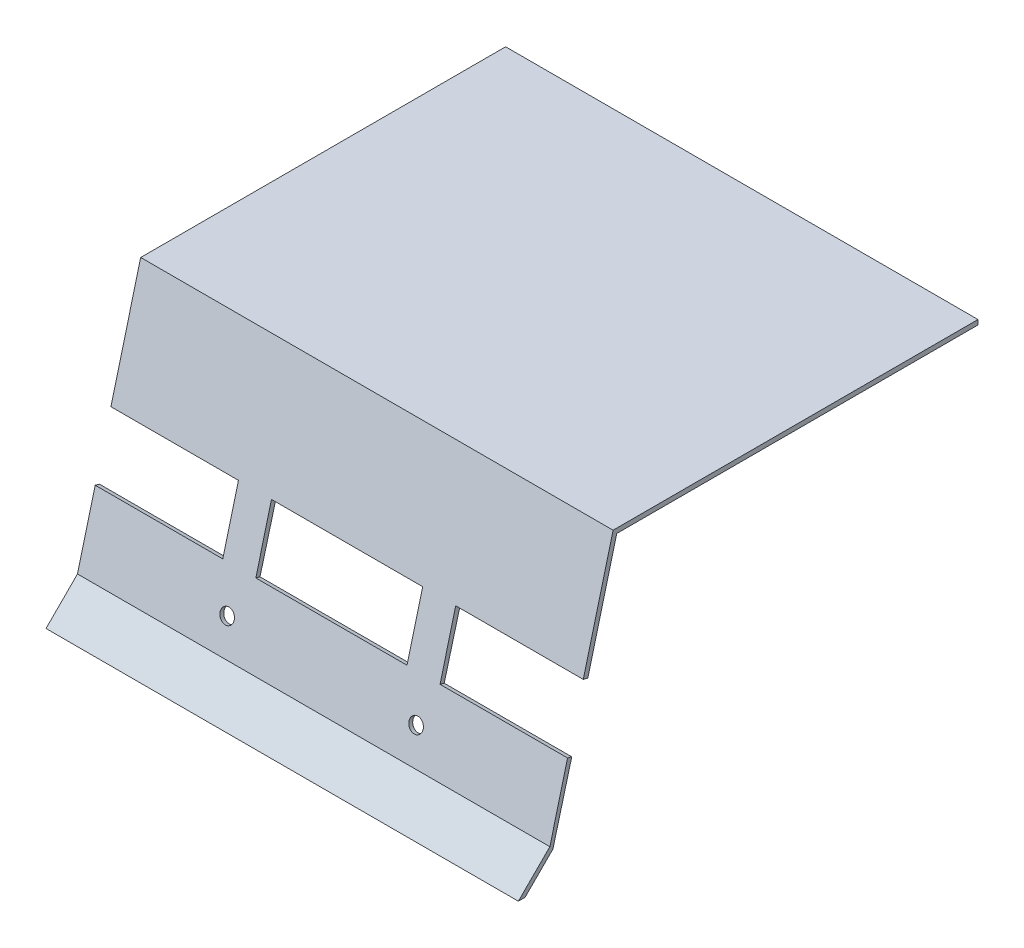
SolidWorks part; units mm, degrees
ref_plane "Plano frontal" through (0, 0, 0) normal (0, 0, 1) x (1, 0, 0)
ref_plane "Plano superior" through (0, 0, 0) normal (0, 1, 0) x (1, 0, 0)
ref_plane "Plano direito" through (0, 0, 0) normal (1, 0, 0) x (0, 0, -1)
sketch "Esboço1" plane through (0, 0, 0) normal (1, 0, 0) x (0, 0, -1)
  line L1 (0, 0) -> (9.2929, 9.2929)
  line L2 (1.4142, 0) -> (10, 8.5858)
  line L6 (15.9689, 32.1111) -> (16.9343, 31.8505)
  line L7 (9.2929, 9.2929) -> (15.9689, 32.1111)
  line L8 (0, 0) -> (1.4142, 0)
  line L9 (10, 8.5858) -> (16.9343, 31.8505)
  dimension "D3" = 1
extrude "Ressalto-extrusão1" add sketch "Esboço1" along normal blind 100
sketch "Esboço2" plane through (100, 0, 0) normal (1, 0, 0) x (0, 0, -1)
  line L1 (7.8161, 7.8161) -> (14.5175, 32.8258)
  line L4 (14.5175, 32.8258) -> (13.5498, 33.0781)
  line L5 (13.5498, 33.0781) -> (6.6654, 6.6654)
  line L6 (9.2929, 9.2929) -> (0, 0) construction
  line L7 (6.6654, 6.6654) -> (7.8161, 7.8161)
  dimension "D2" = 1
extrude "Ressalto-extrusão2" add sketch "Esboço2" against normal blind 100
sketch "Esboço3" plane through (100, 0, 0) normal (1, 0, 0) x (0, 0, -1)
  line L0 (7.2985, 5.8843) -> (7.8161, 7.8161)
  line L1 (1.4142, 0) -> (10, 8.5858) construction
  line L3 (7.8161, 7.8161) -> (9.2929, 9.2929)
  line L4 (9.2929, 9.2929) -> (15.9689, 32.1111)
  line L5 (15.9689, 32.1111) -> (16.9343, 31.8505)
  line L6 (16.9343, 31.8505) -> (10, 8.5858)
  line L7 (10, 8.5858) -> (7.2985, 5.8843)
extrude "Corte-extrusão1" cut sketch "Esboço3" against normal blind 100
sketch "Esboço4" plane through (100, 0, 0) normal (1, 0, 0) x (0, 0, -1)
  line L0 (13.5498, 33.0781) -> (14.5175, 32.8258)
  line L1 (14.5175, 32.8258) -> (19.4044, 51.5749)
  line L2 (19.4044, 51.5749) -> (18.4367, 51.8271)
  line L3 (18.4367, 51.8271) -> (13.5498, 33.0781)
extrude "Ressalto-extrusão3" add sketch "Esboço4" against normal blind 100
sketch "Esboço20" plane through (0, -1.2028, -4.6146) normal (0, 0.2522, 0.9677) x (1, 0, 0)
  circle A0 centre (30, 14.8016) radius 1.5
  circle A1 centre (70, 14.8016) radius 1.5
  dimension "D1" = 3
  dimension "D2" = 3
  dimension "D3" = 40
  dimension "D4" = 40
extrude "Corte-extrusão6" cut sketch "Esboço20" against normal blind 5
ref_plane "Plano1" through (0, 21, -13.2488) normal (1, 0, 0) x (0, 0, -1)
sketch "Esboço24" plane through (0, -1.2028, -4.6146) normal (0, 0.2522, 0.9677) x (1, 0, 0)
  line L2 (0, 36.1686) -> (0, 23.0016)
  line L3 (0, 23.0016) -> (27, 23.0016)
  line L4 (27, 36.1686) -> (27, 23.0016)
  line L6 (100, 36.1686) -> (100, 23.0016)
  line L7 (100, 23.0016) -> (73, 23.0016)
  line L8 (73, 36.1686) -> (73, 23.0016)
  line L10 (34, 36.1686) -> (34, 23.0016)
  line L11 (34, 23.0016) -> (66, 23.0016)
  line L12 (66, 36.1686) -> (66, 23.0016)
  line L13 (0, 36.1686) -> (27, 36.1686)
  line L14 (34, 36.1686) -> (66, 36.1686)
  line L15 (73, 36.1686) -> (100, 36.1686)
extrude "Corte-extrusão7" cut sketch "Esboço24" against normal through all
sketch "Esboço25" plane through (100, 0, 0) normal (1, 0, 0) x (0, 0, -1)
  line L1 (17.5798, 44.5749) -> (10.5472, 44.5749)
  line L2 (10.5472, 44.5749) -> (18.4367, 51.8271)
  line L3 (18.4367, 51.8271) -> (19.4044, 51.5749)
  line L4 (19.4044, 51.5749) -> (17.5798, 44.5749)
  line L5 (14.7047, 33.5443) -> (19.4044, 51.5749) construction
extrude "Corte-extrusão8" cut sketch "Esboço25" against normal through all
sketch "Esboço26" plane through (100, 0, 0) normal (1, 0, 0) x (0, 0, -1)
  line L0 (16.5464, 44.5749) -> (17.5798, 44.5749)
  line L1 (16.5464, 44.5749) -> (13.7371, 33.7965) construction
  line L2 (16.5464, 44.5749) -> (17.5798, 44.5749) construction
  line L3 (14.7047, 33.5443) -> (17.5798, 44.5749) construction
  line L4 (17.5798, 44.5749) -> (20.8184, 57)
  line L5 (20.8184, 57) -> (63.2985, 57)
  line L7 (63.2985, 58) -> (20.0457, 58)
  line L8 (16.5464, 44.5749) -> (20.0457, 58)
  line L10 (63.2985, 57) -> (97.2985, 57)
  line L11 (97.2985, 57) -> (97.2985, 58)
  line L12 (97.2985, 58) -> (63.2985, 58)
extrude "Ressalto-extrusão4" add sketch "Esboço26" against normal blind 100
